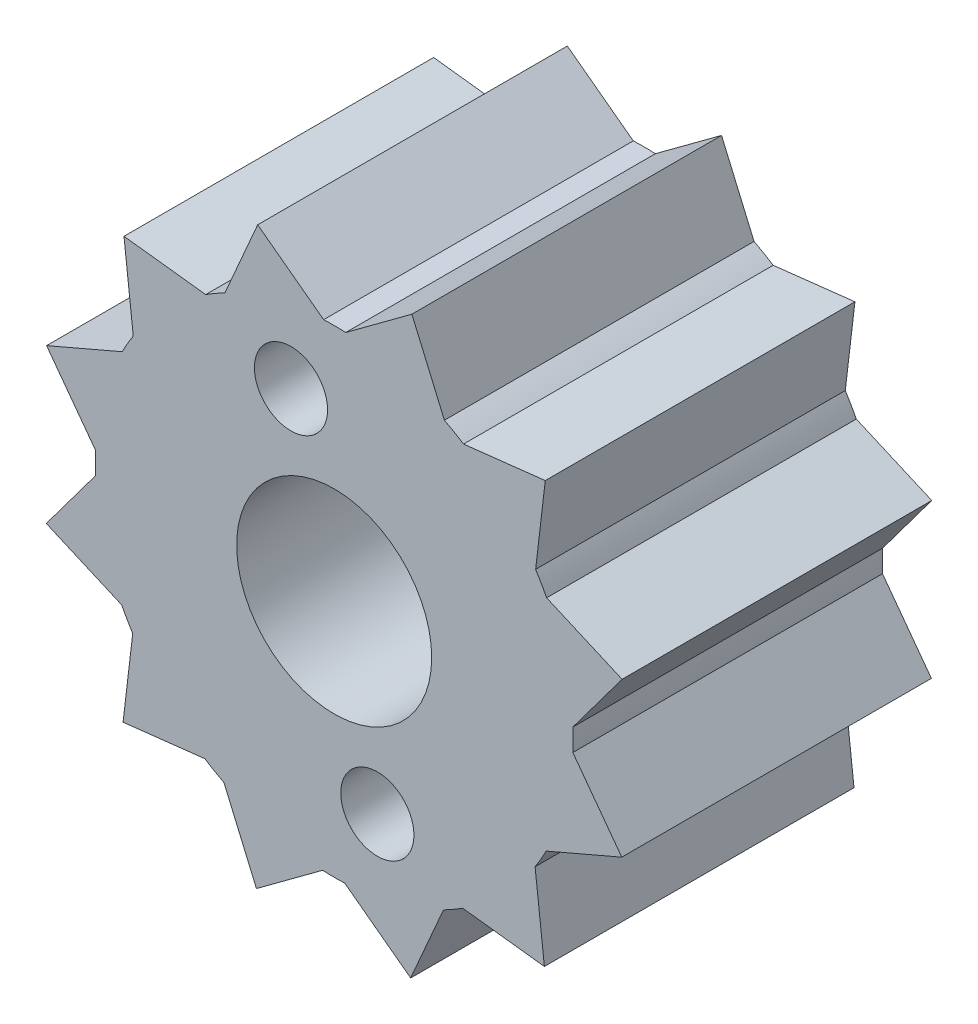
SolidWorks part; units mm, degrees
material "Pine"
ref_plane "Front Plane" through (0, 0, 0) normal (0, 0, 1) x (1, 0, 0)
ref_plane "Top Plane" through (0, 0, 0) normal (0, 1, 0) x (1, 0, 0)
ref_plane "Right Plane" through (0, 0, 0) normal (1, 0, 0) x (0, 0, -1)
sketch "Sketch2" plane through (0, 0, 0) normal (0, 0, 1) x (1, 0, 0)
  line L1 (-5.9042, -1.5686) -> (-4.3571, -2.2419)
  line L2 (-4.1313, -2.6348) -> (-4.3289, -4.3105)
  line L3 (-4.3289, -4.3105) -> (-2.6524, -4.12)
  line L4 (-2.2604, -4.3475) -> (-1.5937, -5.8975)
  line L5 (-1.5937, -5.8975) -> (-0.237, -4.8943)
  line L6 (0.2162, -4.8952) -> (1.5686, -5.9042)
  line L7 (1.5686, -5.9042) -> (2.2419, -4.3571)
  line L8 (2.6348, -4.1313) -> (4.3105, -4.3289)
  line L9 (4.3105, -4.3289) -> (4.12, -2.6524)
  line L10 (4.3475, -2.2604) -> (5.8975, -1.5937)
  line L11 (5.8975, -1.5937) -> (4.8943, -0.237)
  line L12 (4.8952, 0.2162) -> (5.9042, 1.5686)
  line L13 (5.9042, 1.5686) -> (4.3571, 2.2419)
  line L14 (4.1313, 2.6348) -> (4.3289, 4.3105)
  line L15 (4.3289, 4.3105) -> (2.6524, 4.12)
  line L16 (2.2604, 4.3475) -> (1.5937, 5.8975)
  line L17 (1.5937, 5.8975) -> (0.237, 4.8943)
  line L18 (-0.2162, 4.8952) -> (-1.5686, 5.9042)
  line L19 (-1.5686, 5.9042) -> (-2.2419, 4.3571)
  line L20 (-2.6348, 4.1313) -> (-4.3105, 4.3289)
  line L21 (-4.3105, 4.3289) -> (-4.12, 2.6524)
  line L22 (-4.3475, 2.2604) -> (-5.8975, 1.5937)
  line L23 (-5.8975, 1.5937) -> (-4.8943, 0.237)
  line L24 (-4.8952, -0.2162) -> (-5.9042, -1.5686)
  line L25 (-6.0598, -1.6099) -> (-4.4295, -2.3194)
  line L26 (-4.9966, -0.1848) -> (-6.0598, -1.6099)
  line L27 (-6.0529, 1.6357) -> (-4.9958, 0.2061)
  line L28 (-4.4196, 2.3382) -> (-6.0529, 1.6357)
  line L29 (-4.4241, 4.443) -> (-4.2234, 2.6764)
  line L30 (-2.6583, 4.2348) -> (-4.4241, 4.443)
  line L31 (-1.6099, 6.0598) -> (-2.3194, 4.4295)
  line L32 (-0.1848, 4.9966) -> (-1.6099, 6.0598)
  line L33 (1.6357, 6.0529) -> (0.2061, 4.9958)
  line L34 (2.3382, 4.4196) -> (1.6357, 6.0529)
  line L35 (4.443, 4.4241) -> (2.6764, 4.2234)
  line L36 (4.2348, 2.6583) -> (4.443, 4.4241)
  line L37 (6.0598, 1.6099) -> (4.4295, 2.3194)
  line L38 (4.9966, 0.1848) -> (6.0598, 1.6099)
  line L39 (6.0529, -1.6357) -> (4.9958, -0.2061)
  line L40 (4.4196, -2.3382) -> (6.0529, -1.6357)
  line L41 (4.4241, -4.443) -> (4.2234, -2.6764)
  line L42 (2.6583, -4.2348) -> (4.4241, -4.443)
  line L43 (1.6099, -6.0598) -> (2.3194, -4.4295)
  line L44 (0.1848, -4.9966) -> (1.6099, -6.0598)
  line L45 (-1.6357, -6.0529) -> (-0.2061, -4.9958)
  line L46 (-2.3382, -4.4196) -> (-1.6357, -6.0529)
  line L47 (-4.443, -4.4241) -> (-2.6764, -4.2234)
  line L48 (-4.2348, -2.6583) -> (-4.443, -4.4241)
  line L49 (-6.0598, -1.6099) -> (-4.4295, -2.3194) construction
  line L50 (-4.9966, -0.1848) -> (-6.0598, -1.6099) construction
  line L51 (-6.0529, 1.6357) -> (-4.9958, 0.2061) construction
  line L52 (-4.4196, 2.3382) -> (-6.0529, 1.6357) construction
  line L53 (-4.4241, 4.443) -> (-4.2234, 2.6764) construction
  line L54 (-2.6583, 4.2348) -> (-4.4241, 4.443) construction
  line L55 (-1.6099, 6.0598) -> (-2.3194, 4.4295) construction
  line L56 (-0.1848, 4.9966) -> (-1.6099, 6.0598) construction
  line L57 (1.6357, 6.0529) -> (0.2061, 4.9958) construction
  line L58 (2.3382, 4.4196) -> (1.6357, 6.0529) construction
  line L59 (4.443, 4.4241) -> (2.6764, 4.2234) construction
  line L60 (4.2348, 2.6583) -> (4.443, 4.4241) construction
  line L61 (6.0598, 1.6099) -> (4.4295, 2.3194) construction
  line L62 (4.9966, 0.1848) -> (6.0598, 1.6099) construction
  line L63 (6.0529, -1.6357) -> (4.9958, -0.2061) construction
  line L64 (4.4196, -2.3382) -> (6.0529, -1.6357) construction
  line L65 (4.4241, -4.443) -> (4.2234, -2.6764) construction
  line L66 (2.6583, -4.2348) -> (4.4241, -4.443) construction
  line L67 (1.6099, -6.0598) -> (2.3194, -4.4295) construction
  line L68 (0.1848, -4.9966) -> (1.6099, -6.0598) construction
  line L69 (-1.6357, -6.0529) -> (-0.2061, -4.9958) construction
  line L70 (-2.3382, -4.4196) -> (-1.6357, -6.0529) construction
  line L71 (-4.443, -4.4241) -> (-2.6764, -4.2234) construction
  line L72 (-4.2348, -2.6583) -> (-4.443, -4.4241) construction
  arc A0 (-4.3571, -2.2419) -> (-4.1313, -2.6348) centre (0, 0) ccw
  arc A1 (-2.6524, -4.12) -> (-2.2604, -4.3475) centre (0, 0) ccw
  arc A2 (-0.237, -4.8943) -> (0.2162, -4.8952) centre (0, 0) ccw
  arc A3 (2.2419, -4.3571) -> (2.6348, -4.1313) centre (0, 0) ccw
  arc A4 (4.12, -2.6524) -> (4.3475, -2.2604) centre (0, 0) ccw
  arc A5 (4.8943, -0.237) -> (4.8952, 0.2162) centre (0, 0) ccw
  arc A6 (4.3571, 2.2419) -> (4.1313, 2.6348) centre (0, 0) ccw
  arc A7 (2.6524, 4.12) -> (2.2604, 4.3475) centre (0, 0) ccw
  arc A8 (0.237, 4.8943) -> (-0.2162, 4.8952) centre (0, 0) ccw
  arc A9 (-2.2419, 4.3571) -> (-2.6348, 4.1313) centre (0, 0) ccw
  arc A10 (-4.12, 2.6524) -> (-4.3475, 2.2604) centre (0, 0) ccw
  arc A11 (-4.8943, 0.237) -> (-4.8952, -0.2162) centre (0, 0) ccw
  arc A12 (-4.9958, 0.2061) -> (-4.9966, -0.1848) centre (0, 0) ccw
  arc A13 (-4.2234, 2.6764) -> (-4.4196, 2.3382) centre (0, 0) ccw
  arc A14 (-2.3194, 4.4295) -> (-2.6583, 4.2348) centre (0, 0) ccw
  arc A15 (0.2061, 4.9958) -> (-0.1848, 4.9966) centre (0, 0) ccw
  arc A16 (2.6764, 4.2234) -> (2.3382, 4.4196) centre (0, 0) ccw
  arc A17 (4.4295, 2.3194) -> (4.2348, 2.6583) centre (0, 0) ccw
  arc A18 (4.9958, -0.2061) -> (4.9966, 0.1848) centre (0, 0) ccw
  arc A19 (4.2234, -2.6764) -> (4.4196, -2.3382) centre (0, 0) ccw
  arc A20 (2.3194, -4.4295) -> (2.6583, -4.2348) centre (0, 0) ccw
  arc A21 (-0.2061, -4.9958) -> (0.1848, -4.9966) centre (0, 0) ccw
  arc A22 (-2.6764, -4.2234) -> (-2.3382, -4.4196) centre (0, 0) ccw
  arc A23 (-4.4295, -2.3194) -> (-4.2348, -2.6583) centre (0, 0) ccw
  arc A24 (-4.9958, 0.2061) -> (-4.9966, -0.1848) centre (0, 0) ccw construction
  arc A25 (-4.2234, 2.6764) -> (-4.4196, 2.3382) centre (0, 0) ccw construction
  arc A26 (-2.3194, 4.4295) -> (-2.6583, 4.2348) centre (0, 0) ccw construction
  arc A27 (0.2061, 4.9958) -> (-0.1848, 4.9966) centre (0, 0) ccw construction
  arc A28 (2.6764, 4.2234) -> (2.3382, 4.4196) centre (0, 0) ccw construction
  arc A29 (4.4295, 2.3194) -> (4.2348, 2.6583) centre (0, 0) ccw construction
  arc A30 (4.9958, -0.2061) -> (4.9966, 0.1848) centre (0, 0) ccw construction
  arc A31 (4.2234, -2.6764) -> (4.4196, -2.3382) centre (0, 0) ccw construction
  arc A32 (2.3194, -4.4295) -> (2.6583, -4.2348) centre (0, 0) ccw construction
  arc A33 (-0.2061, -4.9958) -> (0.1848, -4.9966) centre (0, 0) ccw construction
  arc A34 (-2.6764, -4.2234) -> (-2.3382, -4.4196) centre (0, 0) ccw construction
  arc A35 (-4.4295, -2.3194) -> (-4.2348, -2.6583) centre (0, 0) ccw construction
  circle A36 centre (0, 0) radius 2
  dimension "D3" = 4
  dimension "D1" = 0
  dimension "D2" = 0.1
extrude "Boss-Extrude1" add sketch "Sketch2" along normal blind 6.35
sketch "Sketch3" plane through (0, 0, 6.35) normal (0, 0, 1) x (1, 0, 0)
  line L0 (-1.5686, 5.9042) -> (1.5686, -5.9042) construction
  line L1 (0, 2) -> (0, 4.9) construction
  circle A0 centre (-0.8858, 3.3343) radius 0.75
  circle A1 centre (0.8858, -3.3343) radius 0.75
  circle A2 centre (0, 0) radius 2 construction
  arc A4 (0.237, 4.8943) -> (-0.2162, 4.8952) centre (0, 0) ccw construction
  circle A6 centre (0, 0) radius 3.45 construction
  point P13 (0, 3.45)
  point P14 (0, 0)
  point P15 (-0.8858, 3.3343)
  point P23 (0.8858, -3.3343)
  dimension "D1" = 1.5
  dimension "D2" = 1.5
extrude "Cut-Extrude1" cut sketch "Sketch3" against normal through all
equation "\"D1@Sketch3\"=\"D2@Sketch3\""
